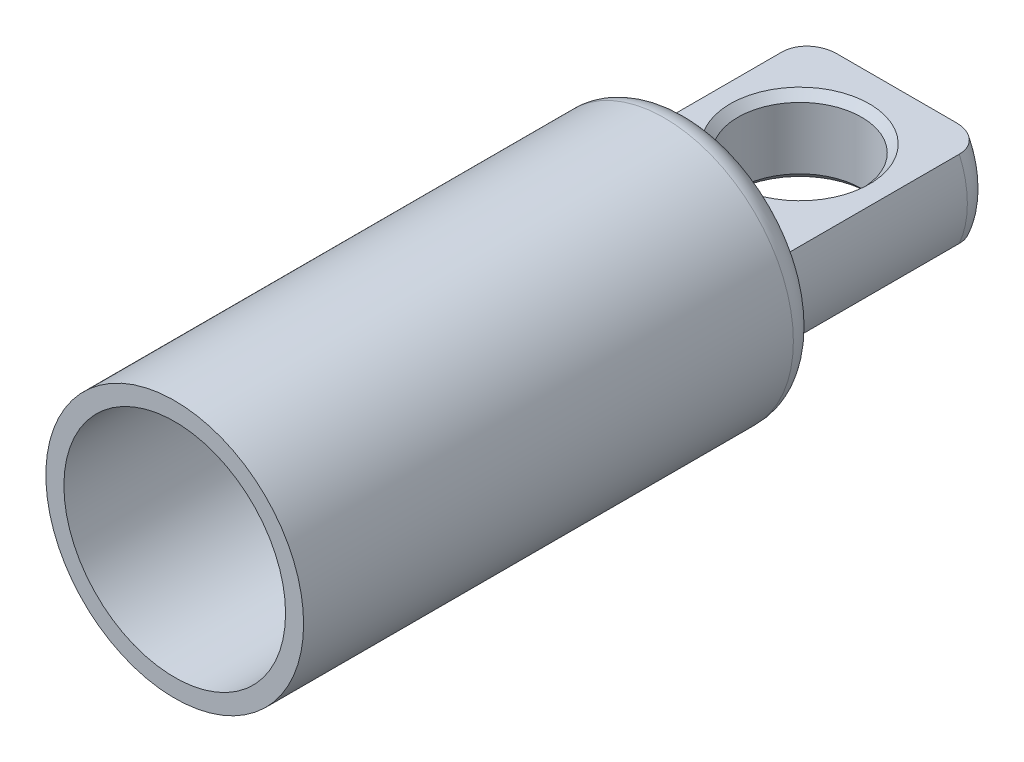
SolidWorks part; units mm, degrees
ref_plane "Front" through (0, 0, 0) normal (0, 0, 1) x (1, 0, 0)
ref_plane "Top" through (0, 0, 0) normal (0, 1, 0) x (1, 0, 0)
ref_plane "Right" through (0, 0, 0) normal (1, 0, 0) x (0, 0, -1)
sketch "Sketch1" plane through (0, 0, 0) normal (0, 0, 1) x (1, 0, 0)
  circle A0 centre (0, 0) radius 6.35
  dimension "D1" = 12.7
extrude "Boss-Extrude1" add sketch "Sketch1" along normal blind 25.4
cosmetic thread "Cosmetic Thread1" parameters "D1"=19.05, "D2"=11.1887
shell "Shell1" thickness 0.889
cosmetic thread "Cosmetic Thread3" parameters "D1"=9.525, "D2"=14.2875
fillet "Fillet1" radius 1.27 1 edges at (6.35, 0, 0)
sketch "Sketch2" plane through (0, 0, 0) normal (0, 0, -1) x (-1, 0, 0)
  circle A0 centre (0, 0) radius 4.7625
  dimension "D1" = 9.525
extrude "Boss-Extrude2" add sketch "Sketch2" along normal blind 10.16
sketch "Sketch3" plane through (0, 0, -10.16) normal (0, 0, -1) x (-1, 0, 0)
  line L0 (-1000, 0) -> (49000, 0) construction
  line L1 (4.3649, 1.905) -> (-4.3649, 1.905)
  line L2 (4.3649, -1.905) -> (-4.3649, -1.905)
  circle A0 centre (0, 0) radius 4.7625 construction
  circle A1 centre (0, 0) radius 4.7625 construction
  arc A2 (4.3649, 1.905) -> (-4.3649, 1.905) centre (0, 0) ccw
  arc A3 (4.3649, -1.905) -> (-4.3649, -1.905) centre (0, 0) cw
  dimension "D1" = 3.81
extrude "Cut-Extrude1" cut sketch "Sketch3" against normal blind 10.16 contours L1 A2 | L2 A3
sketch "Sketch5" plane through (0, 1.905, 0) normal (0, 1, 0) x (1, 0, 0)
  line L0 (-4.3649, 10.16) -> (4.3649, 10.16) construction
  line L1 (-4.3649, 10.16) -> (4.3649, 10.16)
  circle A0 centre (0, 5.3975) radius 3.048
  dimension "D1" = 6.096
  dimension "D2" = 4.7625
extrude "Cut-Extrude2" cut sketch "Sketch5" against normal through all both and the other way through all contours A0
chamfer "Chamfer1" distance 0.381 angle 45 2 edges at (-3.048, -1.905, -5.3975) (-3.048, 1.905, -5.3975)
fillet "Fillet2" radius 1.27 2 edges at (-4.7625, 0, -10.16) (4.7625, 0, -10.16)
